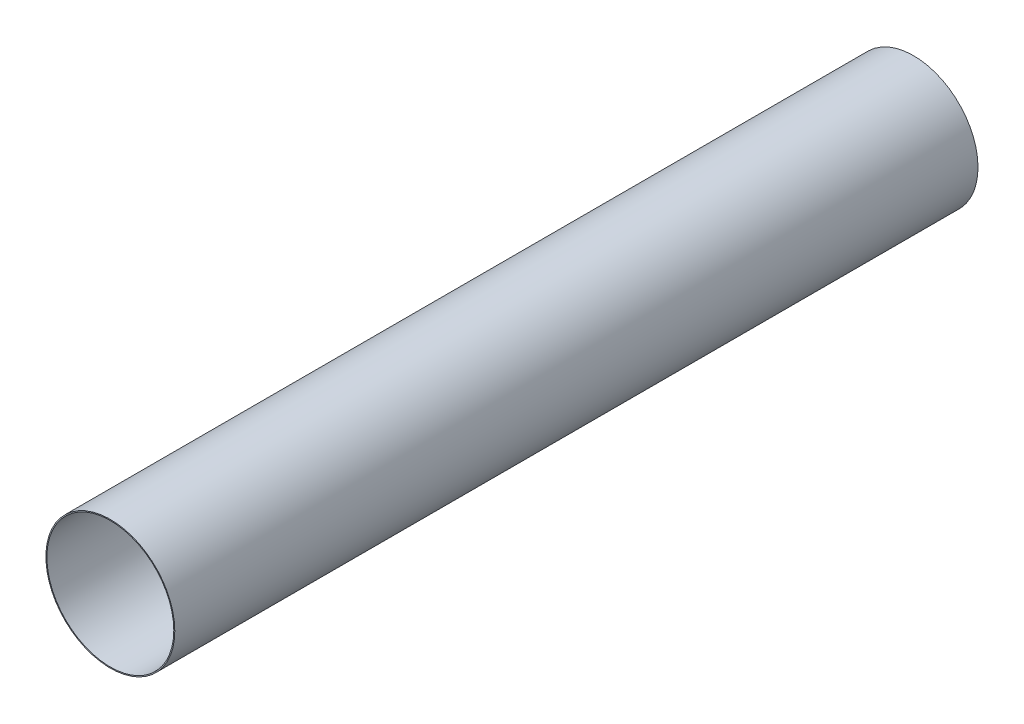
SolidWorks part; units mm, degrees
ref_plane "Plan de face" through (0, 0, 0) normal (0, 0, 1) x (1, 0, 0)
ref_plane "Plan de dessus" through (0, 0, 0) normal (0, 1, 0) x (1, 0, 0)
ref_plane "Plan de droite" through (0, 0, 0) normal (1, 0, 0) x (0, 0, -1)
sketch "Esquisse1" plane through (0, 0, 0) normal (0, 0, 1) x (1, 0, 0)
  circle A2 centre (0, 0) radius 76.182
  circle A3 centre (0, 0) radius 75
  dimension "D1" = 150
  dimension "D2" = 152.364
extrude "Boss.-Extru.1" add sketch "Esquisse1" along normal blind 949.3 contours A2 | A3
equation "\"d_i_tube\"= 150mm'Inner Rocket Body Composite Tube Diameter"
equation "\"t_tube\"= 1.182mm'Thickness of Rocket Body Composite Tube"
equation "\"l_upper_body_tube\"= 949.3mm'Upper Rocket Body Composite Tube length"
equation "\"l_lower_body_tube\"= 816mm'Lower Rocket Body Composite Tube Length"
equation "\"d_a_NC\"= 154mm'Outer Diameter of Nosecone base"
equation "\"d_i_phenolic_tube\"= 152.3mm'Inner Phenolic Tube Diameter"
equation "\"t_phenolic_tube\"= 2mm'Thickness of Phenolic Body Tube"
equation "\"l_fin_cut\"= 220mm'Length of fin on Motor Retainer"
equation "\"t_SW-Panel\"= 11.482mm'Thickness of Sandwich-Panel"
equation "\"l_motor_tube\"=610mm'Length of phenolic motor tube"
equation "\"d_i_motor_tube\"=99.06mm'Inner diameter of phenolic motor tube"
equation "\"t_motor_tube\"=1.58mm'Thicknes of phenolic motor tube"
equation "\"l_cut_fin_centering\"=13mm'Length of cut for fin alignement on fin centering rings"
equation "\"l_M3_threaded_rods\"=220mm'Length of M3 threaded rods for thrust plate force transmission"
equation "\"D1@Esquisse1\"=\"d_i_tube\""
equation "\"D2@Esquisse1\"=\"d_i_tube\"+\"t_tube\"*2"
equation "\"D1@Boss.-Extru.1\"=\"l_upper_body_tube\""
